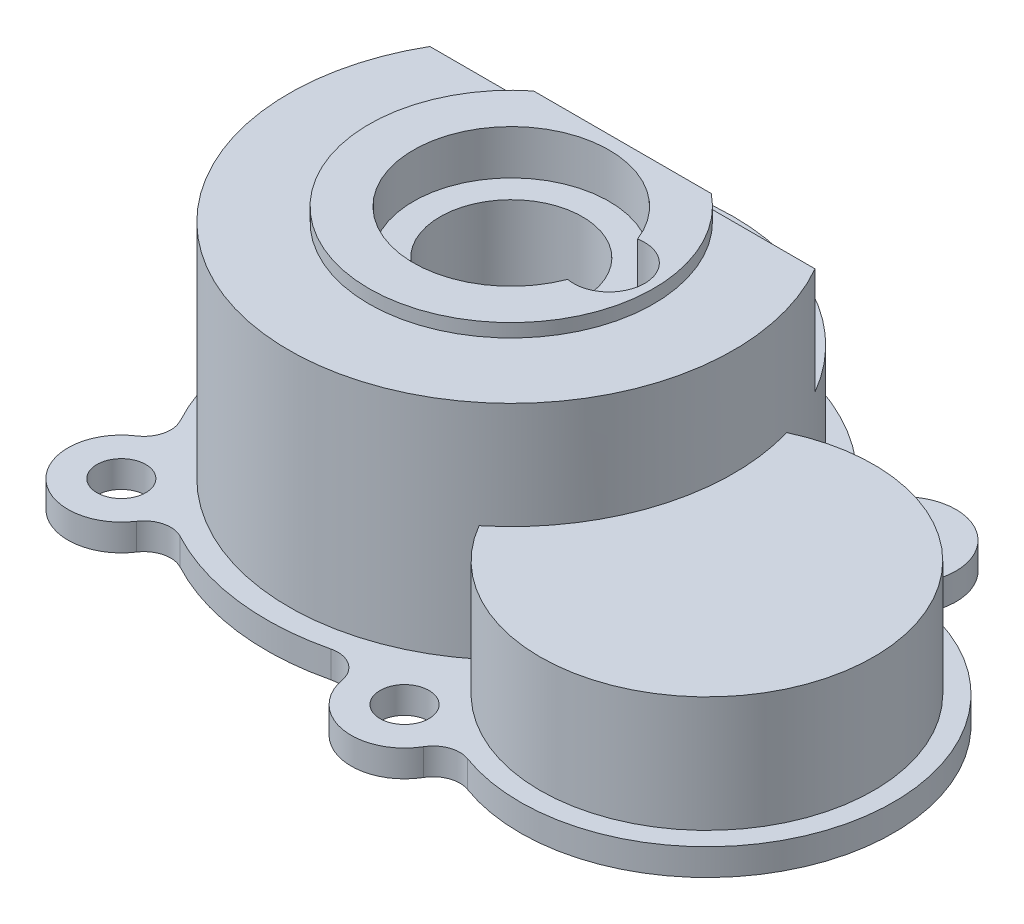
SolidWorks part; units mm, degrees
ref_plane "Front" through (0, 0, 0) normal (0, 0, 1) x (1, 0, 0)
ref_plane "Top" through (0, 0, 0) normal (0, 1, 0) x (1, 0, 0)
ref_plane "Right" through (0, 0, 0) normal (1, 0, 0) x (0, 0, -1)
sketch "Sketch1" plane through (0, 0, 0) normal (0, 1, 0) x (1, 0, 0)
  arc A0 (21.2118, -50.745) -> (43.9652, -56.9135) centre (32, -56) ccw
  arc A2 (62.5978, 21.9766) -> (44.0376, 32.9497) centre (56, 32) ccw
  arc A3 (44.0376, 32.9497) -> (-31.8805, 44.8178) centre (0, 0) ccw
  arc A4 (43.9652, -56.9135) -> (62.5978, 21.9766) centre (64, -20) ccw
  arc A5 (-31.8805, 44.8178) -> (-44.8178, 31.8805) centre (-43.8406, 43.8406) ccw
  arc A6 (-44.8178, 31.8805) -> (-44.8178, -31.8805) centre (0, 0) ccw
  arc A7 (-44.8178, -31.8805) -> (-31.8805, -44.8178) centre (-43.8406, -43.8406) ccw
  arc A8 (-31.8805, -44.8178) -> (21.2118, -50.745) centre (0, 0) ccw
extrude "Boss-Extrude1" add sketch "Sketch1" along normal blind 6 contours A4 A2 A3 A5 A6 A7 A8 A0
sketch "Sketch2" plane through (0, 6, 0) normal (0, 1, 0) x (1, 0, 0)
  circle A0 centre (56, 32) radius 5.5
  circle A1 centre (-43.8406, 43.8406) radius 5.5
  circle A2 centre (-43.8406, -43.8406) radius 5.5
  circle A3 centre (32, -56) radius 5.5
extrude "Cut-Extrude1" cut sketch "Sketch2" against normal blind 6
sketch "Sketch3" plane through (0, 6, 0) normal (0, 1, 0) x (1, 0, 0)
  line L0 (0, 0) -> (0, 59.0026) construction
  line L1 (0, 0) -> (0, -41.1369) construction
  line L2 (0, 0) -> (35.3117, 0) construction
  line L3 (0, 0) -> (-36.6479, 0) construction
  line L4 (64, 11.5529) -> (64, -83.8564) construction
  line L5 (28.2197, -20) -> (103.3395, -20) construction
  circle A0 centre (0, 0) radius 50
  dimension "D1" = 64
  dimension "D2" = 20
extrude "Boss-Extrude2" add sketch "Sketch3" along normal blind 50
sketch "Sketch4" plane through (0, 6, 0) normal (0, 1, 0) x (1, 0, 0)
  line L0 (0, 0) -> (0, 42.5643) construction
  line L1 (0, 0) -> (0, -43.3175) construction
  line L2 (0, 0) -> (47.892, 0) construction
  line L3 (64, 2.1395) -> (64, -71.4975) construction
  line L4 (54.4338, -20) -> (102.0714, -20) construction
  line L5 (31.5477, -38.791) -> (117.2265, -38.791) construction
  line L6 (31.5477, -38.791) -> (-1.2681, -38.791) construction
  line L7 (48.0217, 13.9255) -> (126.1389, 13.9255) construction
  line L8 (48.0217, 13.9255) -> (6.0239, 13.9255) construction
  circle A0 centre (64, -20) radius 37.5
  circle A1 centre (0, 0) radius 50 construction
  circle A2 centre (0, 0) radius 50 construction
  dimension "D1" = 64
  dimension "D2" = 20
extrude "Boss-Extrude3" add sketch "Sketch4" along normal blind 26 contours A0
sketch "Sketch5" plane through (0, 56, 0) normal (0, 1, 0) x (1, 0, 0)
  circle A0 centre (0, 0) radius 32
extrude "Boss-Extrude4" add sketch "Sketch5" along normal blind 3
fillet "Fillet2" radius 6 1 edges at (44.0376, 3, -32.9497)
fillet "Fillet3" radius 6 7 edges at (-44.8178, 3, -31.8805) (-44.8178, 3, 31.8805) (-31.8805, 3, 44.8178) (21.2118, 3, 50.745) (43.9652, 3, 56.9135) (62.5978, 3, -21.9766) (-31.8805, 3, -44.8178)
sketch "Sketch6" plane through (0, 59, 0) normal (0, 1, 0) x (1, 0, 0)
  line L0 (0, 0) -> (0, 25) construction
  line L1 (0, 25) -> (43.3013, 25)
  line L2 (0, 25) -> (-43.3013, 25)
  circle A0 centre (0, 0) radius 50 construction
  arc A1 (-43.3013, 25) -> (43.3013, 25) centre (0, 0) cw
extrude "Cut-Extrude2" cut sketch "Sketch6" against normal blind 27
sketch "Sketch7" plane through (0, 59, 0) normal (0, 1, 0) x (1, 0, 0)
  line L0 (0, 0) -> (22, 0) construction
  arc A0 (20.5455, 7.8667) -> (20.5455, -7.8667) centre (0, 0) ccw
  arc A1 (20.5455, -7.8667) -> (20.5455, 7.8667) centre (22, 0) ccw
extrude "Cut-Extrude3" cut sketch "Sketch7" against normal blind 10
sketch "Sketch12" plane through (0, 0, 0) normal (0, -1, 0) x (1, 0, 0)
  circle A0 centre (64, 20) radius 33
extrude "Cut-Extrude9" cut sketch "Sketch12" against normal blind 29
sketch "Sketch21" plane through (0, 56, 0) normal (0, 1, 0) x (1, 0, 0)
  circle A0 centre (0, 0) radius 16
extrude "Cut-Extrude16" cut sketch "Sketch21" against normal blind 35
sketch "Sketch22" plane through (0, 0, 0) normal (0, -1, 0) x (1, 0, 0)
  circle A0 centre (0, 0) radius 45
extrude "Cut-Extrude18" cut sketch "Sketch22" against normal blind 21 contours A0
sketch "Sketch34" plane through (0, 21, 0) normal (0, -1, 0) x (-1, 0, 0)
  circle A0 centre (0, 0) radius 25
  circle A1 centre (0, 0) radius 45
extrude "Cut-Extrude25" cut sketch "Sketch34" against normal blind 8
sketch "Sketch35" plane through (0, 29, 0) normal (0, -1, 0) x (1, 0, 0)
  line L1 (15, -20) -> (40.3113, -20)
  line L2 (-15, -20) -> (-40.3113, -20)
  arc A0 (40.3113, -20) -> (-40.3113, -20) centre (0, 0) ccw
  arc A1 (15, -20) -> (24.3864, -5.505) centre (0, 0) ccw
  arc A2 (24.3864, -5.505) -> (24.3864, 5.505) centre (22, 0) ccw
  arc A3 (24.3864, 5.505) -> (-15, -20) centre (0, 0) ccw
extrude "Cut-Extrude26" cut sketch "Sketch35" against normal blind 13
